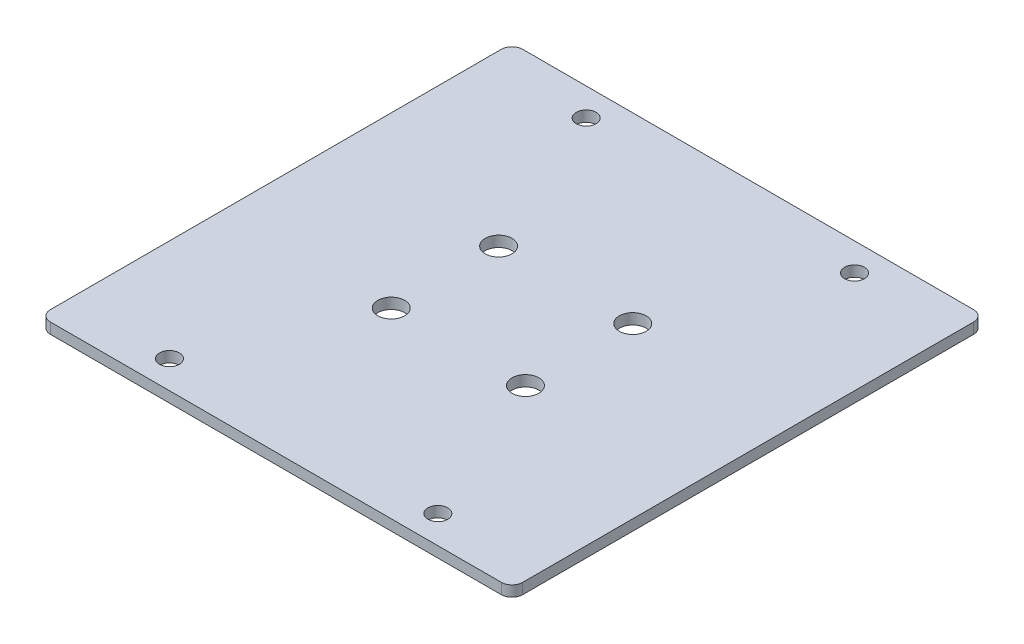
SolidWorks part; units mm, degrees
material "Acrylic (Medium-high impact)"
ref_plane "Front Plane" through (0, 0, 0) normal (0, 0, 1) x (1, 0, 0)
ref_plane "Top Plane" through (0, 0, 0) normal (0, 1, 0) x (1, 0, 0)
ref_plane "Right Plane" through (0, 0, 0) normal (1, 0, 0) x (0, 0, -1)
sketch "Sketch1" plane through (0, 0, 0) normal (0, 1, 0) x (1, 0, 0)
  line L1 (44, -44) -> (-44, -44)
  line L2 (44, -44) -> (44, 44)
  line L3 (44, 44) -> (-44, 44)
  line L4 (-44, -44) -> (-44, 44)
  line L5 (44, -44) -> (-44, 44) construction
  line L6 (44, 44) -> (-44, -44) construction
  point P0 (0, 0)
  dimension "D1" = 88
  dimension "D2" = 88
extrude "Boss-Extrude1" add sketch "Sketch1" along normal blind 2
fillet "Fillet1" radius 2 4 edges at (-44, 1, -44) (44, 1, -44) (-44, 1, 44) (44, 1, 44)
sketch "Sketch3" plane through (0, 2, 0) normal (0, 1, 0) x (1, 0, 0)
  circle A0 centre (-25, 38.82) radius 1.85
  circle A1 centre (25, 38.82) radius 1.85
  circle A2 centre (-25, -38.82) radius 1.85
  circle A3 centre (25, -38.82) radius 1.85
  dimension "D1" = 3.7
extrude "Cut-Extrude1" cut sketch "Sketch3" against normal blind 10
sketch "Sketch4" plane through (0, 2, 0) normal (0, 1, 0) x (1, 0, 0)
  circle A0 centre (-12.5, 10) radius 2.5
  circle A1 centre (-12.5, -10) radius 2.5
  circle A2 centre (12.5, -10) radius 2.5
  circle A3 centre (12.5, 10) radius 2.5
  dimension "D1" = 5
extrude "Cut-Extrude2" cut sketch "Sketch4" against normal blind 10
